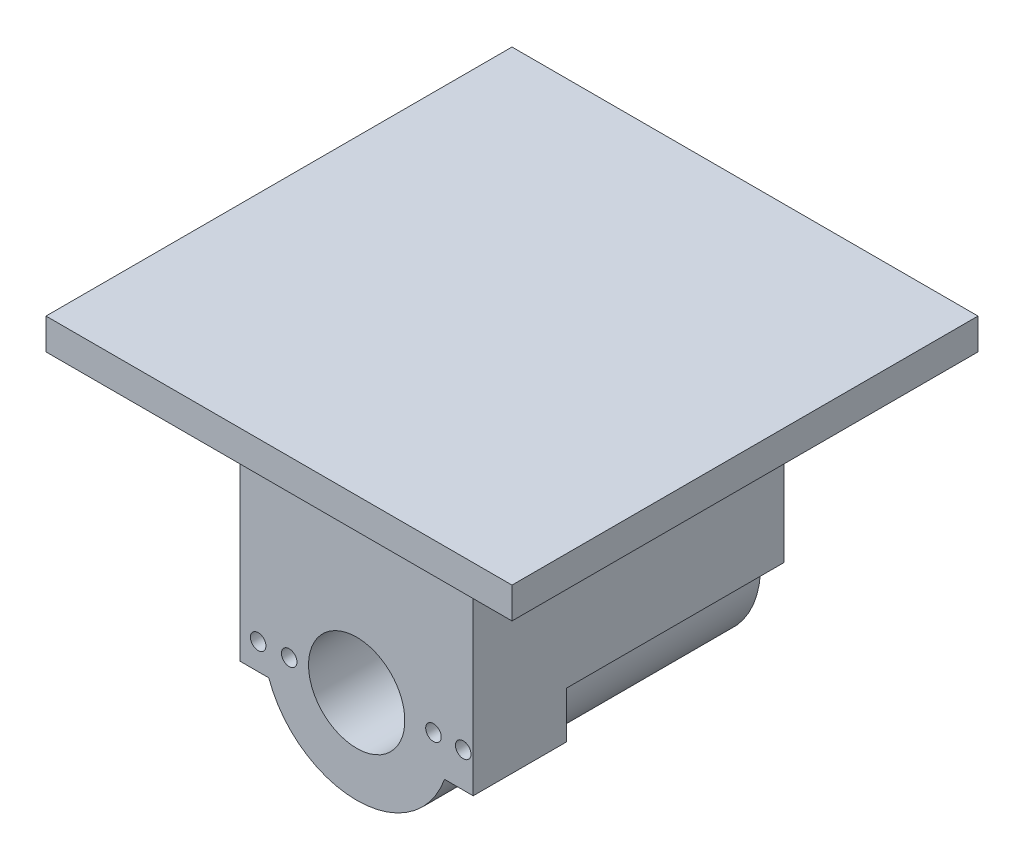
SolidWorks part; units mm, degrees
ref_plane "Ön Düzlem" through (0, 0, 0) normal (0, 0, 1) x (1, 0, 0)
ref_plane "Üst Düzlem" through (0, 0, 0) normal (0, 1, 0) x (1, 0, 0)
ref_plane "Sağ Düzlem" through (0, 0, 0) normal (1, 0, 0) x (0, 0, -1)
sketch "Sketch1" plane through (0, 0, 0) normal (0, 0, 1) x (1, 0, 0)
  circle A0 centre (0, 0) radius 6
  dimension "D1" = 12
extrude "Boss-Extrude1" add sketch "Sketch1" along normal blind 20
sketch "Sketch2" plane through (0, 0, 0) normal (0, 1, 0) x (1, 0, 0)
  line L0 (-6, -20) -> (6, -20) construction
  line L1 (7.5, 0) -> (-7.5, 0)
  line L2 (7.5, 0) -> (7.5, -20)
  line L3 (7.5, -20) -> (-7.5, -20)
  line L4 (-7.5, 0) -> (-7.5, -20)
  line L5 (7.5, 0) -> (-7.5, -20) construction
  line L6 (7.5, -20) -> (-7.5, 0) construction
  line L7 (6, 0) -> (-6, 0) construction
  point P0 (0, -10)
  dimension "D1" = 15
extrude "Boss-Extrude2" add sketch "Sketch2" along normal blind 5 from offset 1
sketch "Sketch3" plane through (0, 0, 0) normal (0, 0, -1) x (-1, 0, 0)
  circle A1 centre (0, 0) radius 3.1
  dimension "D1" = 6.2
extrude "Cut-Extrude1" cut sketch "Sketch3" against normal through all
sketch "Sketch4" plane through (0, 0, 20) normal (0, 0, 1) x (1, 0, 0)
  line L0 (5.6569, -2) -> (7.5, -2)
  line L1 (7.5, -2) -> (7.5, 1)
  line L2 (-5.6569, -2) -> (-7.5, -2)
  line L3 (-7.5, -2) -> (-7.5, 1)
  line L5 (5.9161, 1) -> (7.5, 1)
  line L6 (7.5, 1) -> (7.5, 6)
  line L7 (7.5, 6) -> (-7.5, 6)
  line L8 (-7.5, 6) -> (-7.5, 1)
  line L9 (-7.5, 1) -> (-5.9161, 1)
  line L10 (5.9161, 1) -> (7.5, 1)
  line L11 (7.5, 1) -> (7.5, 6)
  line L12 (7.5, 6) -> (-7.5, 6)
  line L13 (-7.5, 6) -> (-7.5, 1)
  line L14 (-7.5, 1) -> (-5.9161, 1)
  arc A1 (-5.9161, 1) -> (5.9161, 1) centre (0, 0) ccw
  arc A2 (-5.9161, 1) -> (5.9161, 1) centre (0, 0) ccw
  arc M10 (-5.9161, 1) -> (5.9161, 1) centre (0, 0) ccw
  line M11 (5.9161, 1) -> (7.5, 1)
  line M15 (-7.5, 1) -> (-5.9161, 1)
  dimension "D2" = 3
  dimension "D1" = 0
extrude "Boss-Extrude3" add sketch "Sketch4" against normal blind 6 contours L0 L1 M11 M10 | L3 L2 M10 M15
sketch "Sketch5" plane through (0, 0, 20) normal (0, 0, 1) x (1, 0, 0)
  circle A0 centre (-6.3419, -0.3198) radius 0.5
  circle A1 centre (-4.3445, -0.2191) radius 0.5
  circle A2 centre (4.9437, 0.2493) radius 0.5
  circle A3 centre (6.8604, 0.2493) radius 0.5
extrude "Cut-Extrude2" cut sketch "Sketch5" against normal blind 10
sketch "Sketch6" plane through (0, 6, 0) normal (0, 1, 0) x (1, 0, 0)
  line L0 (7.5, 0) -> (7.5, -20)
  line L1 (7.5, 0) -> (-7.5, 0)
  line L2 (7.5, -20) -> (-7.5, -20)
  line L3 (-7.5, 0) -> (-7.5, -20)
  line L4 (7.5, -20) -> (7.5, 0) construction
  line L5 (-7.5, 0) -> (-7.5, -20) construction
  point P8 (-7.5, -10)
  point P9 (-7.5, -10)
  dimension "D1" = 20
extrude "Boss-Extrude4" add sketch "Sketch6" along normal blind 8
sketch "Sketch7" plane through (0, 14, 0) normal (0, 1, 0) x (1, 0, 0)
  line L0 (-7.5, -20) -> (7.5, -20) construction
  line L1 (-15, -25) -> (15, -25)
  line L2 (-15, -25) -> (-15, 5)
  line L3 (-15, 5) -> (15, 5)
  line L4 (15, -25) -> (15, 5)
  line L5 (-15, -25) -> (15, 5) construction
  line L6 (-15, 5) -> (15, -25) construction
  line L7 (-7.5, 0) -> (-7.5, -20) construction
  point P0 (0, -10)
  point P8 (0, -20)
  point P12 (-7.5, -10)
  dimension "D1" = 30
  dimension "D2" = 30
extrude "Boss-Extrude5" add sketch "Sketch7" along normal blind 2
fillet "Fillet1" radius 3 4 edges at (7.5, 14, 10) (0, 14, 20) (-7.5, 14, 10) (0, 14, 0)
